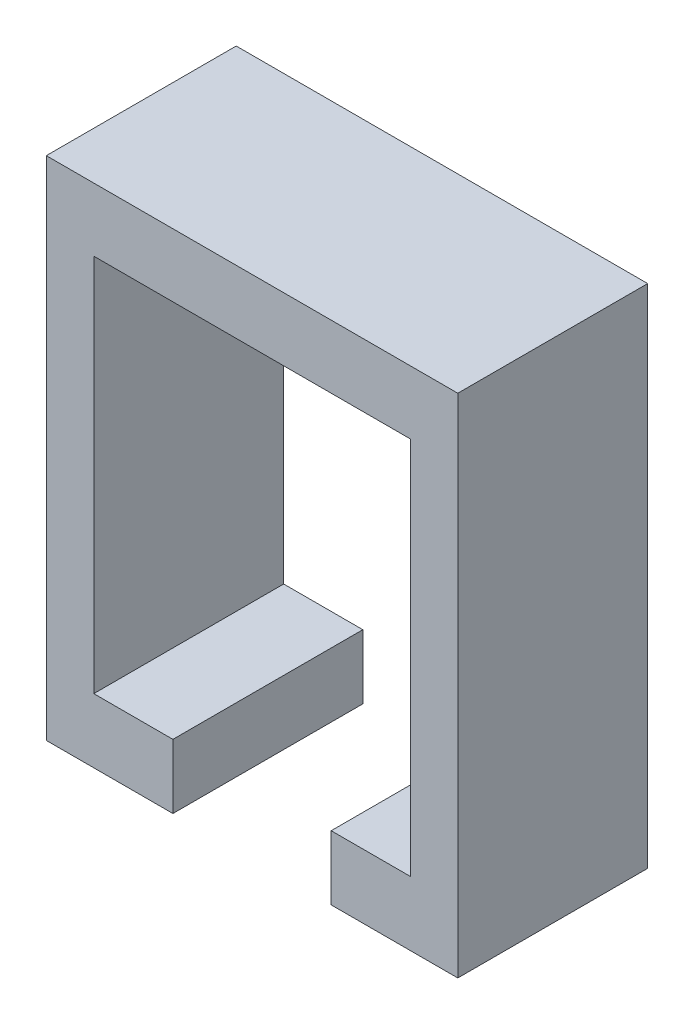
SolidWorks part; units mm, degrees
ref_plane "Front Plane" through (0, 0, 0) normal (0, 0, 1) x (1, 0, 0)
ref_plane "Top Plane" through (0, 0, 0) normal (0, 1, 0) x (1, 0, 0)
ref_plane "Right Plane" through (0, 0, 0) normal (1, 0, 0) x (0, 0, -1)
sketch "Sketch1" plane through (0, 0, 0) normal (0, 0, 1) x (1, 0, 0)
  line L1 (-5, -2) -> (-5, -13.97)
  line L2 (-5, -2) -> (5, -2)
  line L3 (5, -2) -> (5, -13.97)
  line L5 (-6.5, -16) -> (-6.5, 0)
  line L8 (-6.5, 0) -> (6.5, 0)
  line L11 (6.5, 0) -> (6.5, -16)
  line L12 (-5, -13.97) -> (-2.5, -13.97)
  line L13 (-2.5, -13.97) -> (-2.5, -16)
  line L14 (-2.5, -16) -> (-6.5, -16)
  line L15 (5, -13.97) -> (2.5, -13.97)
  line L16 (2.5, -13.97) -> (2.5, -16)
  line L17 (2.5, -16) -> (6.5, -16)
  point P11 (0, 0)
  point P18 (0, -2)
  dimension "D1" = 10
  dimension "D2" = 16
  dimension "D3" = 11.97
  dimension "D4" = 2
  dimension "D5" = 5
  dimension "D6" = 1.5
  dimension "D7" = 11.97
extrude "Boss-Extrude1" add sketch "Sketch1" along normal blind 6
